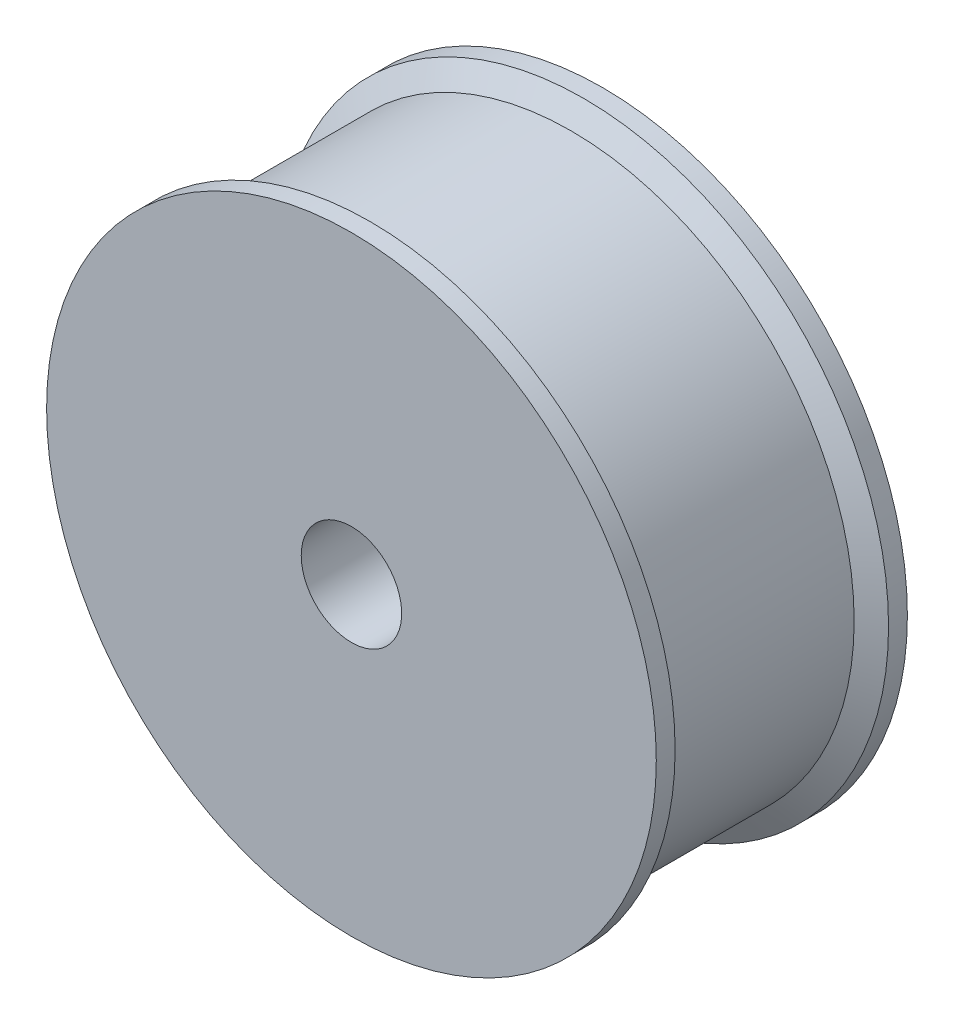
SolidWorks part; units mm, degrees
ref_plane "Přední rovina" through (0, 0, 0) normal (0, 0, 1) x (1, 0, 0)
ref_plane "Horní rovina" through (0, 0, 0) normal (0, 1, 0) x (1, 0, 0)
ref_plane "Pravá rovina" through (0, 0, 0) normal (1, 0, 0) x (0, 0, -1)
sketch "Skica1" plane through (0, 0, 0) normal (1, 0, 0) x (0, 0, -1)
  line L0 (0, 0) -> (-31.8265, 0) construction
  line L1 (0, 4) -> (0, 16.5)
  line L2 (-10, 24.28) -> (-11.5, 24.28)
  line L3 (-11.5, 24.28) -> (-12.5, 22.54)
  line L4 (-12.5, 22.54) -> (-27.5, 22.54)
  line L5 (-27.5, 22.54) -> (-28.5, 24.28)
  line L6 (-28.5, 24.28) -> (-30, 24.28)
  line L7 (-30, 24.28) -> (-30, 4)
  line L8 (-28.5, 24.28) -> (-11.5, 24.28) construction
  line L9 (-30, 4) -> (0, 4)
  line L10 (-20, 24.28) -> (-20, 22.54) construction
  line L11 (-10, 24.28) -> (-10, 16.5)
  line L12 (-10, 16.5) -> (0, 16.5)
  dimension "D1" = 1.74
  dimension "D2" = 45.08
  dimension "D3" = 30
  dimension "D4" = 15
  dimension "D5" = 17
  dimension "D6" = 8
  dimension "D7" = 20
  dimension "D8" = 18.54
  dimension "D9" = 33
revolve "Rotovat1" add sketch "Skica1" angle 360 about L0
sketch "Skica2" plane through (0, 0, 0) normal (1, 0, 0) x (0, 0, -1)
  line L0 (-10, -16.5) -> (0, -16.5) construction
  line L1 (0, 16.5) -> (-8, 16.5)
  line L2 (0, 16.5) -> (0, -16.5)
  line L3 (0, -16.5) -> (-8, -16.5)
  line L4 (-8, 16.5) -> (-8, -16.5)
  dimension "D1" = 8
extrude "Odebrat vysunutím1" cut sketch "Skica2" against normal mid plane 70
move or copy body "Tělo-Přesunout/kopírovat1" [suppressed] bodies to move or copy 102
